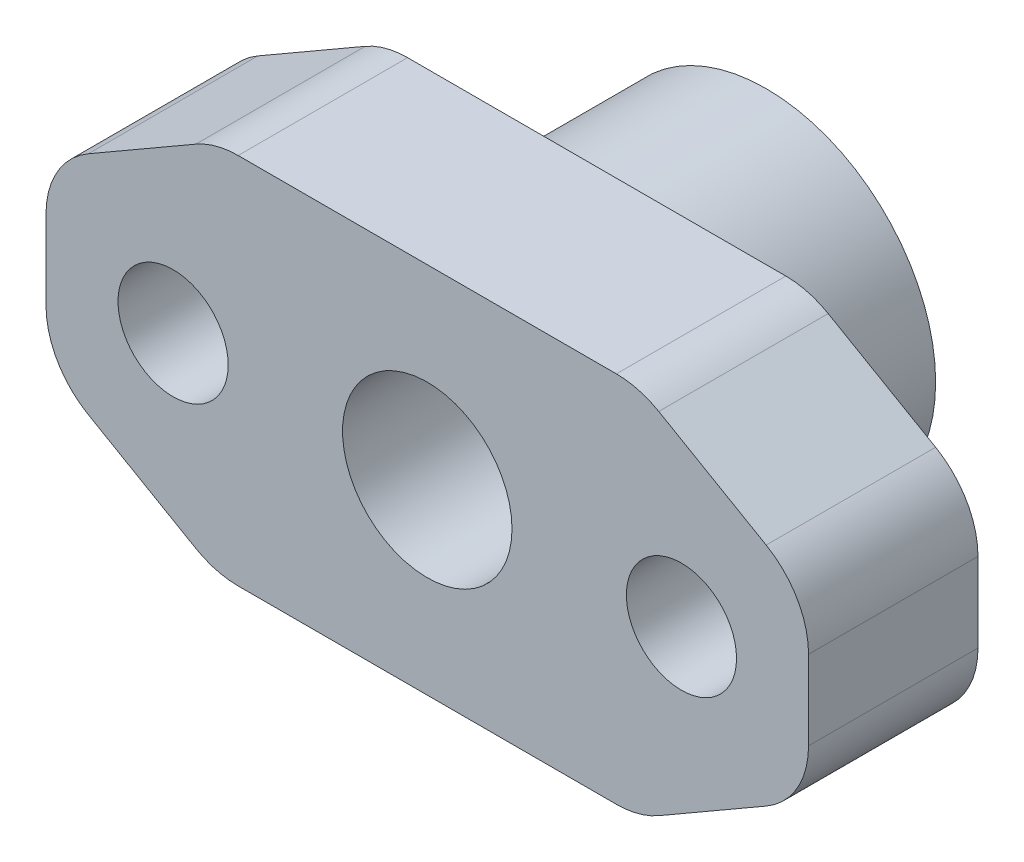
SolidWorks part; units mm, degrees
ref_plane "Plan de face" through (0, 0, 0) normal (0, 0, 1) x (1, 0, 0)
ref_plane "Plan de dessus" through (0, 0, 0) normal (0, 1, 0) x (1, 0, 0)
ref_plane "Plan de droite" through (0, 0, 0) normal (1, 0, 0) x (0, 0, -1)
sketch "Esquisse1" plane through (0, 0, 0) normal (0, 0, 1) x (1, 0, 0)
  circle A0 centre (0, 0) radius 5
  circle A1 centre (0, 0) radius 10
  dimension "D1" = 10
  dimension "D2" = 20
extrude "Boss.-Extru.1" add sketch "Esquisse1" along normal blind 20
sketch "Esquisse2" plane through (0, 0, 20) normal (0, 0, 1) x (1, 0, 0)
  line L0 (-22.5, 0) -> (22.5, 0) construction
  line L1 (22.5, -5.2265) -> (22.5, 5.2265)
  line L2 (22.5, 5.2265) -> (12.5, 11)
  line L3 (12.5, 11) -> (-12.5, 11)
  line L4 (0, 11) -> (0, 0) construction
  line L5 (22.5, -5.2265) -> (12.5, -11)
  line L6 (12.5, -11) -> (-12.5, -11)
  line L7 (-22.5, -5.2265) -> (-12.5, -11)
  line L8 (-22.5, 5.2265) -> (-12.5, 11)
  line L9 (-22.5, -5.2265) -> (-22.5, 5.2265)
  circle A0 centre (0, 0) radius 5
  circle A1 centre (0, 0) radius 5 construction
  point P11 (0, -11)
  dimension "D1" = 22
  dimension "D2" = 45
  dimension "D3" = 120
  dimension "D4" = 10
extrude "Boss.-Extru.2" add sketch "Esquisse2" against normal blind 10
sketch "Esquisse3" plane through (0, 0, 20) normal (0, 0, 1) x (1, 0, 0)
  line L0 (0, 0) -> (0, 10.8429) construction
  line L1 (0, 0) -> (15, 0) construction
  circle A0 centre (15, 0) radius 3.25
  circle A1 centre (-15, 0) radius 3.25
  dimension "D1" = 6.5
  dimension "D2" = 30
extrude "Enlèv. mat.-Extru.1" cut sketch "Esquisse3" against normal through all both and the other way through all
fillet "Congé1" radius 5 8 edges at (-22.5, 5.2265, 15) (-22.5, -5.2265, 15) (22.5, -5.2265, 15) (22.5, 5.2265, 15) (12.5, -11, 15) (-12.5, -11, 15) (-12.5, 11, 15) (12.5, 11, 15)
